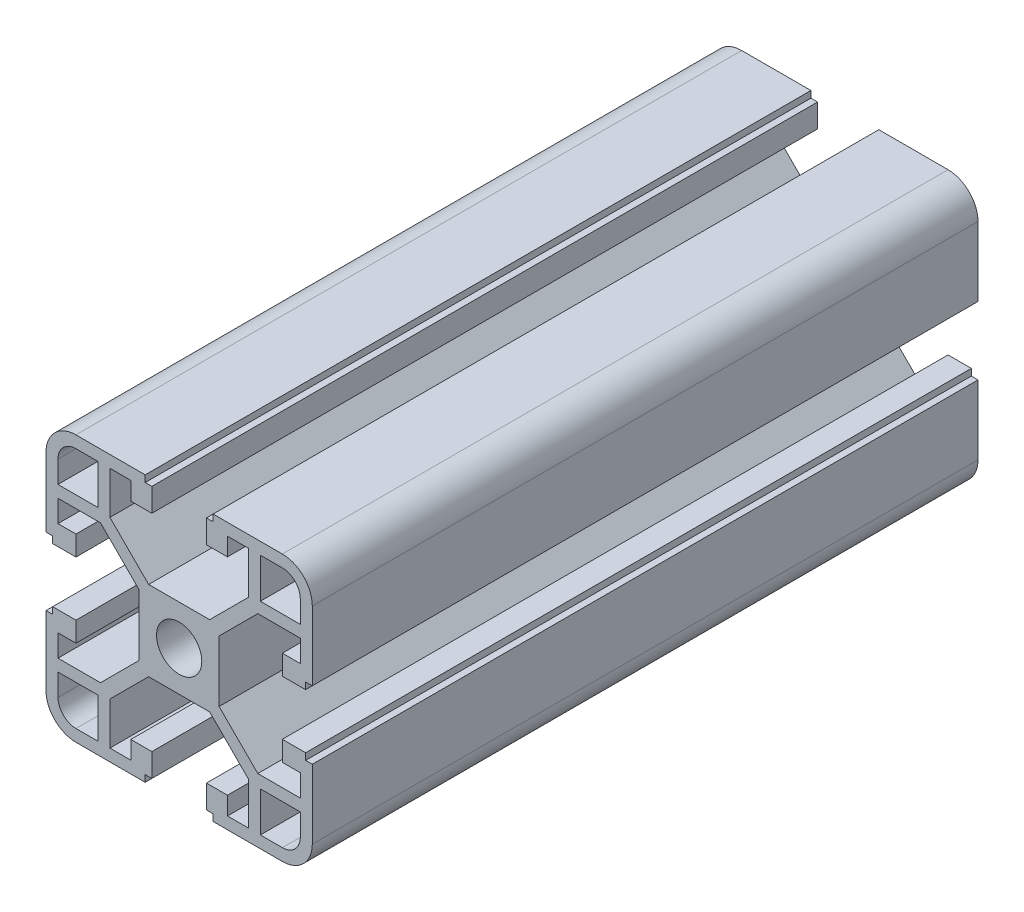
SolidWorks part; units mm, degrees
material "6063-T5"
ref_plane "Front Plane" through (0, 0, 0) normal (0, 0, 1) x (1, 0, 0)
ref_plane "Top Plane" through (0, 0, 0) normal (0, 1, 0) x (1, 0, 0)
ref_plane "Right Plane" through (0, 0, 0) normal (1, 0, 0) x (0, 0, -1)
sketch "Sketch3" plane through (0, 0, 0) normal (0, 0, 1) x (1, 0, 0)
  line L0 (17.9333, 92.7) -> (169.2667, 92.7) construction
  line L1 (-6, 6) -> (6, 6)
  line L2 (-6, 6) -> (-6, -6)
  line L3 (-6, -6) -> (6, -6)
  line L4 (6, 6) -> (6, -6)
  line L5 (0, 0) -> (20.1249, 20.1249) construction
  line L6 (4.5736, 4.5736) -> (11.4537, 11.4537) construction
  line L7 (5.2807, 3.8665) -> (12.0153, 10.6011)
  line L8 (3.8665, 5.2807) -> (10.7858, 12.2)
  line L13 (11.8142, 10.4) -> (18.2, 10.4)
  line L14 (6, 0) -> (23.1042, 0) construction
  line L15 (0, 6) -> (0, 13.9346) construction
  line L16 (4.5736, 4.5736) -> (11.8129, 11.8129) construction
  line L17 (5.2807, 3.8665) -> (12.52, 11.1058) construction
  line L18 (3.8665, 5.2807) -> (11.1058, 12.52) construction
  line L19 (10.4, 11.8142) -> (10.4, 18.2)
  line L20 (10.4, 18.2) -> (7.2581, 18.2)
  line L21 (-20, 20) -> (20, 20) construction
  line L22 (-20, 20) -> (-20, -20) construction
  line L23 (-20, -20) -> (20, -20) construction
  line L24 (20, 20) -> (20, -20) construction
  line L25 (7.2581, 18.2) -> (7.2581, 15.5)
  line L26 (7.2581, 15.5) -> (4.1, 15.5)
  line L27 (4.1, 15.5) -> (4.1, 19)
  line L28 (4.1, 19) -> (5.1, 19)
  line L29 (5.1, 19) -> (5.1, 20)
  line L30 (5.1, 20) -> (15.5, 20)
  line L31 (20, 15.5) -> (20, 5.1)
  line L32 (20, 5.1) -> (19, 5.1)
  line L33 (19, 5.1) -> (19, 4.1)
  line L34 (19, 4.1) -> (15.5, 4.1)
  line L35 (15.5, 4.1) -> (15.5, 7.1)
  line L36 (15.5, 7.1) -> (18.2, 7.1)
  line L37 (18.2, 7.1) -> (18.2, 10.4)
  line L42 (18.2, 12.2) -> (12.2, 12.2)
  line L43 (12.2, 18.2) -> (12.2, 18.2)
  line L44 (12.2, 18.2) -> (12.2, 18.2)
  line L45 (12.2, 18.2) -> (12.2, 18.2)
  line L46 (12.2, 18.2) -> (12.2, 18.2)
  line L47 (12.2, 18.2) -> (12.2, 18.2)
  line L48 (12.2, 18.2) -> (12.2, 18.2)
  line L49 (12.2, 18.2) -> (15.5, 18.2)
  line L50 (18.2, 15.5) -> (18.2, 12.2)
  line L51 (18.2, 12.2) -> (18.2, 12.2)
  line L52 (18.2, 12.2) -> (18.2, 12.2)
  line L53 (18.2, 12.2) -> (18.2, 12.2)
  line L54 (18.2, 12.2) -> (18.2, 12.2)
  line L55 (18.2, 12.2) -> (18.2, 12.2)
  line L56 (18.2, 12.2) -> (18.2, 12.2)
  line L57 (12.2, 12.2) -> (12.2, 18.2)
  line L58 (11.8142, 12.2) -> (18.2, 12.2) construction
  line L59 (12.2, 11.8142) -> (12.2, 18.2) construction
  line L60 (-18.2, 15.5) -> (-18.2, 12.2)
  line L61 (-12.2, 18.2) -> (-15.5, 18.2)
  line L62 (-12.2, 12.2) -> (-12.2, 18.2)
  line L63 (-18.2, 12.2) -> (-12.2, 12.2)
  line L64 (-11.8142, 10.4) -> (-18.2, 10.4)
  line L65 (-18.2, 7.1) -> (-18.2, 10.4)
  line L66 (-15.5, 7.1) -> (-18.2, 7.1)
  line L67 (-15.5, 4.1) -> (-15.5, 7.1)
  line L68 (-19, 4.1) -> (-15.5, 4.1)
  line L69 (-19, 5.1) -> (-19, 4.1)
  line L70 (-20, 5.1) -> (-19, 5.1)
  line L71 (-20, 15.5) -> (-20, 5.1)
  line L72 (-5.1, 20) -> (-15.5, 20)
  line L73 (-5.1, 19) -> (-5.1, 20)
  line L74 (-4.1, 19) -> (-5.1, 19)
  line L75 (-4.1, 15.5) -> (-4.1, 19)
  line L76 (-7.2581, 15.5) -> (-4.1, 15.5)
  line L77 (-7.2581, 18.2) -> (-7.2581, 15.5)
  line L78 (-10.4, 18.2) -> (-7.2581, 18.2)
  line L79 (-10.4, 11.8142) -> (-10.4, 18.2)
  line L80 (-10.4, 11.8142) -> (-4.5858, 6)
  line L81 (-11.8142, 10.4) -> (-6, 4.5858)
  line L82 (-18.2, -15.5) -> (-18.2, -12.2)
  line L83 (-18.2, -12.2) -> (-12.2, -12.2)
  line L84 (-12.2, -12.2) -> (-12.2, -18.2)
  line L85 (-12.2, -18.2) -> (-15.5, -18.2)
  line L86 (-20, -15.5) -> (-20, -5.1)
  line L87 (-20, -5.1) -> (-19, -5.1)
  line L88 (-19, -5.1) -> (-19, -4.1)
  line L89 (-19, -4.1) -> (-15.5, -4.1)
  line L90 (-15.5, -4.1) -> (-15.5, -7.1)
  line L91 (-15.5, -7.1) -> (-18.2, -7.1)
  line L92 (-18.2, -7.1) -> (-18.2, -10.4)
  line L93 (-11.8142, -10.4) -> (-18.2, -10.4)
  line L94 (-11.8142, -10.4) -> (-6, -4.5858)
  line L95 (-10.4, -11.8142) -> (-4.5858, -6)
  line L96 (-10.4, -11.8142) -> (-10.4, -18.2)
  line L97 (-10.4, -18.2) -> (-7.2581, -18.2)
  line L98 (-7.2581, -18.2) -> (-7.2581, -15.5)
  line L99 (-7.2581, -15.5) -> (-4.1, -15.5)
  line L100 (-4.1, -15.5) -> (-4.1, -19)
  line L101 (-4.1, -19) -> (-5.1, -19)
  line L102 (-5.1, -19) -> (-5.1, -20)
  line L103 (-5.1, -20) -> (-15.5, -20)
  line L104 (12.2, -18.2) -> (15.5, -18.2)
  line L105 (12.2, -12.2) -> (12.2, -18.2)
  line L106 (18.2, -12.2) -> (12.2, -12.2)
  line L107 (18.2, -15.5) -> (18.2, -12.2)
  line L108 (5.1, -20) -> (15.5, -20)
  line L109 (5.1, -19) -> (5.1, -20)
  line L110 (4.1, -19) -> (5.1, -19)
  line L111 (4.1, -15.5) -> (4.1, -19)
  line L112 (7.2581, -15.5) -> (4.1, -15.5)
  line L113 (10.4, -18.2) -> (7.2581, -18.2)
  line L114 (7.2581, -18.2) -> (7.2581, -15.5)
  line L115 (10.4, -11.8142) -> (10.4, -18.2)
  line L116 (10.4, -11.8142) -> (4.5858, -6)
  line L117 (11.8142, -10.4) -> (6, -4.5858)
  line L118 (11.8142, -10.4) -> (18.2, -10.4)
  line L119 (18.2, -7.1) -> (18.2, -10.4)
  line L120 (20, -15.5) -> (20, -5.1)
  line L121 (20, -5.1) -> (19, -5.1)
  line L122 (19, -5.1) -> (19, -4.1)
  line L123 (15.5, -7.1) -> (18.2, -7.1)
  line L124 (15.5, -4.1) -> (15.5, -7.1)
  line L125 (19, -4.1) -> (15.5, -4.1)
  circle A0 centre (0, 0) radius 3.4
  arc A1 (15.5, 20) -> (20, 15.5) centre (15.5, 15.5) cw
  arc A2 (15.5, 18.2) -> (18.2, 15.5) centre (15.5, 15.5) cw
  arc A3 (-15.5, 18.2) -> (-18.2, 15.5) centre (-15.5, 15.5) ccw
  arc A4 (-15.5, 20) -> (-20, 15.5) centre (-15.5, 15.5) ccw
  arc A5 (-15.5, -18.2) -> (-18.2, -15.5) centre (-15.5, -15.5) cw
  arc A6 (-15.5, -20) -> (-20, -15.5) centre (-15.5, -15.5) cw
  arc A7 (15.5, -18.2) -> (18.2, -15.5) centre (15.5, -15.5) ccw
  arc A8 (15.5, -20) -> (20, -15.5) centre (15.5, -15.5) ccw
  point P7 (6, 0)
  point P8 (0, 6)
  point P36 (0, 20)
  point P37 (-20, 0)
  dimension "D3" = 6.8
  dimension "D28" = 4.5
  dimension "D1" = 12
  dimension "D2" = 12
  dimension "D6" = 10.4
  dimension "D7" = 10.4
  dimension "D8" = 40
  dimension "D9" = 40
  dimension "D10" = 1
  dimension "D11" = 1
  dimension "D12" = 1.8
  dimension "D13" = 1.8
  dimension "D14" = 2
  dimension "D17" = 1.8
  dimension "D18" = 1.8
  dimension "D19" = 1
  dimension "D20" = 1
  dimension "D21" = 3.5
  dimension "D22" = 5.1
  dimension "D23" = 4.1
  dimension "D24" = 3
  dimension "D25" = 3.5
  dimension "D26" = 4.1
  dimension "D27" = 5.1
  dimension "D4" = 1
  dimension "D5" = 1
  dimension "D29" = 1.8
extrude "Boss-Extrude1" add sketch "Sketch3" along normal blind 100
